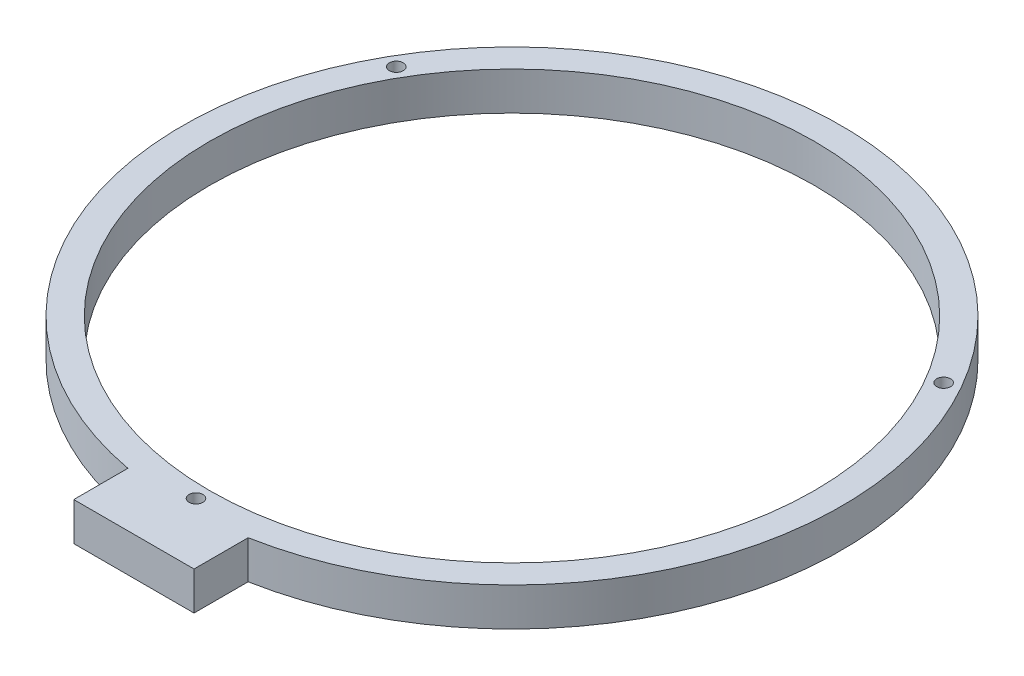
SolidWorks part; units mm, degrees
ref_plane "Front Plane" through (0, 0, 0) normal (0, 0, 1) x (1, 0, 0)
ref_plane "Top Plane" through (0, 0, 0) normal (0, 1, 0) x (1, 0, 0)
ref_plane "Right Plane" through (0, 0, 0) normal (1, 0, 0) x (0, 0, -1)
sketch "Sketch1" plane through (0, 0, 0) normal (0, 1, 0) x (1, 0, 0)
  line L0 (-10, -53.8799) -> (-10, -62.8799)
  line L1 (-10, -62.8799) -> (10, -62.8799)
  line L2 (10, -62.8799) -> (10, -53.8799)
  arc A0 (10, -53.8799) -> (-10, -53.8799) centre (0, 0) ccw
  circle A1 centre (0, 0) radius 50.3
  point P9 (0, -62.8799)
  dimension "D1" = 4.5
  dimension "D2" = 109.6
  dimension "D3" = 20
  dimension "D4" = 9
extrude "Boss-Extrude1" add sketch "Sketch1" along normal blind 6.35
sketch "Sketch2" plane through (0, 6.35, 0) normal (0, 1, 0) x (1, 0, 0)
  line L0 (0, -50.3) -> (0, -54.8) construction
  circle A0 centre (0, 0) radius 50.3 construction
  circle A1 centre (0, 0) radius 54.8 construction
  circle A2 centre (0, -52.55) radius 1.15
  dimension "D1" = 2.3
extrude "Cut-Extrude1" cut sketch "Sketch2" against normal up to next
pattern_circular "CirPattern1" count 3 over 360 about axis through (0, 0, 0) along (0, 1, 0) of "Cut-Extrude1"
